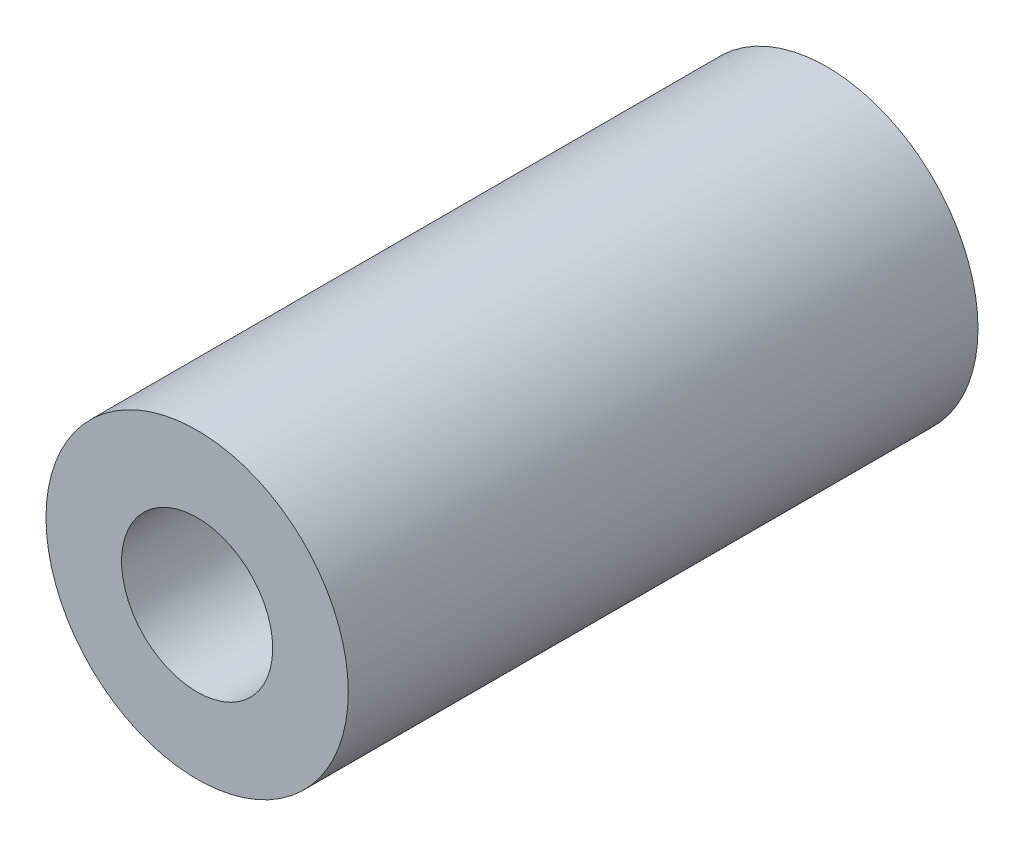
SolidWorks part; units mm, degrees
ref_plane "Ön Düzlem" through (0, 0, 0) normal (0, 0, 1) x (1, 0, 0)
ref_plane "Üst Düzlem" through (0, 0, 0) normal (0, 1, 0) x (1, 0, 0)
ref_plane "Sağ Düzlem" through (0, 0, 0) normal (1, 0, 0) x (0, 0, -1)
sketch "Çizim1" plane through (0, 0, 0) normal (0, 0, 1) x (1, 0, 0)
  circle A0 centre (0, 0) radius 3
  circle A1 centre (0, 0) radius 6
extrude "Yükseklik-Ekstrüzyon1" add sketch "Çizim1" along normal blind 25
